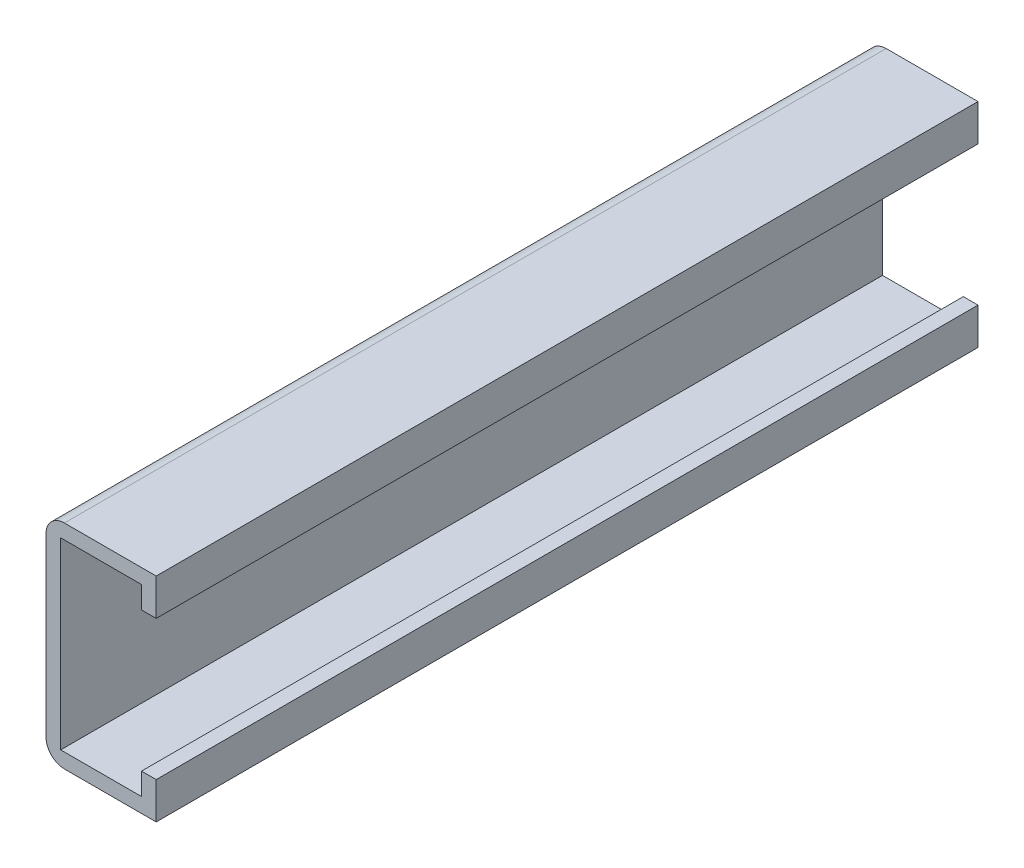
SolidWorks part; units mm, degrees
ref_plane "Alzado" through (0, 0, 0) normal (0, 0, 1) x (1, 0, 0)
ref_plane "Planta" through (0, 0, 0) normal (0, 1, 0) x (1, 0, 0)
ref_plane "Vista lateral" through (0, 0, 0) normal (1, 0, 0) x (0, 0, -1)
sketch "Croquis1" plane through (0, 0, 0) normal (0, 0, 1) x (1, 0, 0)
  line L17 (11, 19) -> (15, 19)
  line L18 (-15, 29) -> (15, 29)
  line L19 (-15, 29) -> (-15, -29)
  line L20 (-15, -29) -> (15, -29)
  line L21 (15, 29) -> (15, 19)
  line L22 (-11, 25) -> (11, 25)
  line L23 (-11, 25) -> (-11, -25)
  line L24 (-11, -25) -> (11, -25)
  line L25 (11, 25) -> (11, 19)
  line L26 (11, -19) -> (15, -19)
  line L27 (15, -19) -> (15, -29)
  line L28 (11, -19) -> (11, -25)
  point P12 (0, 25)
  point P13 (-11, 0)
  point P14 (-15, 0)
  point P15 (0, 29)
  dimension "D1" = 4
  dimension "D2" = 4
  dimension "D3" = 6
  dimension "D4" = 22
  dimension "D5" = 50
extrude "Saliente-Extruir1" add sketch "Croquis1" against normal blind 223.76
fillet "Redondeo2" radius 5 2 edges at (-15, -29, -111.88) (-15, 29, -111.88)
